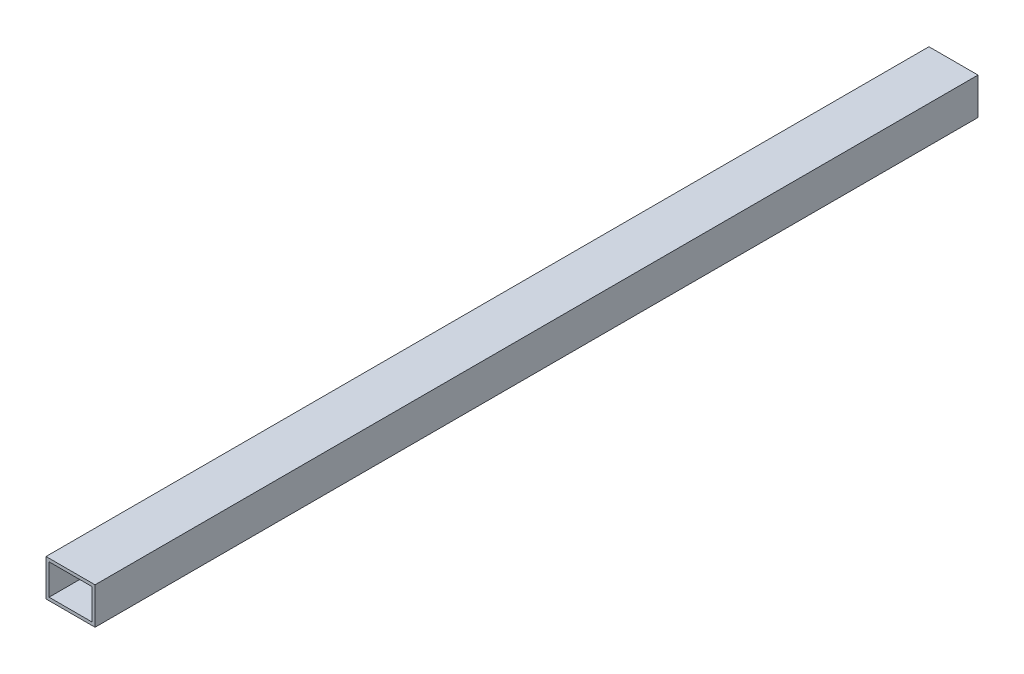
SolidWorks part; units mm, degrees
ref_plane "Front Plane" through (0, 0, 0) normal (0, 0, 1) x (1, 0, 0)
ref_plane "Top Plane" through (0, 0, 0) normal (0, 1, 0) x (1, 0, 0)
ref_plane "Right Plane" through (0, 0, 0) normal (1, 0, 0) x (0, 0, -1)
sketch "Sketch1" plane through (0, 0, 0) normal (0, 0, 1) x (1, 0, 0)
  line L0 (25.4, 0) -> (22.225, 0) construction
  line L1 (-25.4, 0) -> (25.4, 0) construction
  line L2 (0, 19.05) -> (0, -19.05)
  point P7 (0, 0)
sketch "Sketch2" plane through (0, 0, 0) normal (1, 0, 0) x (0, 0, -1)
  line L0 (457.2, 0) -> (-457.2, 0)
  point P4 (0, 0)
  dimension "Length" = 914.4
sketch "Sketch3" plane through (0, 0, 0) normal (0, 0, 1) x (1, 0, 0)
  line L0 (-25.4, 0) -> (25.4, 0) construction
  line L5 (25.4, -19.05) -> (-25.4, -19.05)
  line L6 (25.4, -19.05) -> (25.4, 19.05)
  line L11 (25.4, 19.05) -> (-25.4, 19.05)
  line L12 (-25.4, -19.05) -> (-25.4, 19.05)
  line L14 (25.4, -19.05) -> (-25.4, 19.05) construction
  line L15 (25.4, 19.05) -> (-25.4, -19.05) construction
  line L16 (22.225, -15.875) -> (-22.225, -15.875)
  line L17 (22.225, -15.875) -> (22.225, 15.875)
  line L18 (22.225, 15.875) -> (-22.225, 15.875)
  line L19 (-22.225, -15.875) -> (-22.225, 15.875)
  line L20 (22.225, -15.875) -> (-22.225, 15.875) construction
  line L21 (22.225, 15.875) -> (-22.225, -15.875) construction
  point P0 (0, 0)
  point P5 (0, 0)
  point P13 (22.225, -19.05)
  dimension "D1" = 3.175
  dimension "D3" = 50.8
  dimension "D4" = 38.1
  dimension "D2" = 3.175
extrude "Boss-Extrude1" add sketch "Sketch3" along normal up to vertex (457.2 mm away) and the other way up to vertex (457.2 mm away) up to point (0, 0, 457.2) other way up to point (0, 0, -457.2)
sketch "Sketch5" plane through (0, 0, 0) normal (1, 0, 0) x (0, 0, -1)
  line L0 (-457.2, 0) -> (457.2, 0) construction
  line L3 (-457.2, -19.05) -> (-457.2, 19.05) construction
  line L4 (457.2, -19.05) -> (457.2, 19.05) construction
  point P6 (-400.05, 0)
  point P7 (-381, 0)
  point P8 (381, 0)
  point P10 (400.05, 0)
  dimension "D1" = 57.15
  dimension "D2" = 76.2
  dimension "D3" = 57.15
  dimension "D4" = 76.2
sketch "Sketch7" plane through (0, -19.05, 0) normal (0, -1, 0) x (1, 0, 0)
  line L0 (0, 457.2) -> (0, -254)
  line L1 (-25.4, 457.2) -> (25.4, 457.2) construction
  point P6 (0, -254)
  dimension "D1" = 711.2
equation "\"D1@Sketch3\"=\"Wall thickness@Sketch1\""
equation "\"D1@Sketch5\"=\"Width@Sketch1\"*1.125"
equation "\"D2@Sketch5\"=\"Width@Sketch1\"*1.5"
equation "\"D3@Sketch5\"=\"D1@Sketch5\""
equation "\"D4@Sketch5\"=\"D2@Sketch5\""
equation "\"D2@Sketch3\"=\"Wall Thickness@Sketch1\""
equation "\"actuatorDistanceFromTop\" = 28"
equation "\"D1@Sketch7\"=\"actuatorDistanceFromTop\""
